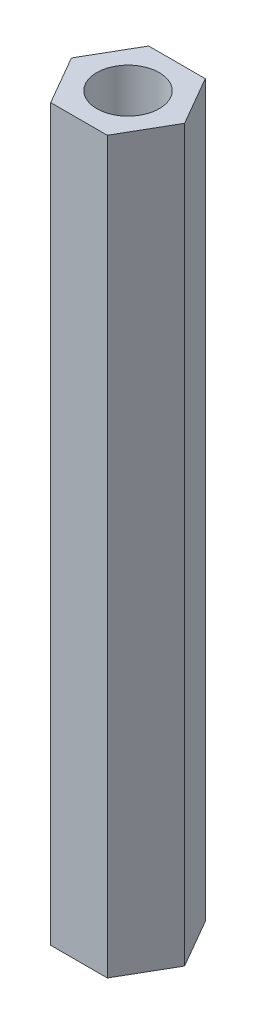
SolidWorks part; units mm, degrees
material "Brass"
ref_plane "Front Plane" through (0, 0, 0) normal (0, 0, 1) x (1, 0, 0)
ref_plane "Top Plane" through (0, 0, 0) normal (0, 1, 0) x (1, 0, 0)
ref_plane "Right Plane" through (0, 0, 0) normal (1, 0, 0) x (0, 0, -1)
sketch "Sketch1" plane through (0, 0, 0) normal (0, 1, 0) x (1, 0, 0)
  line L1 (2.7135, 0) -> (1.3568, 2.35)
  line L2 (1.3568, 2.35) -> (-1.3568, 2.35)
  line L3 (-1.3568, 2.35) -> (-2.7135, 0)
  line L4 (-2.7135, 0) -> (-1.3568, -2.35)
  line L5 (-1.3568, -2.35) -> (1.3568, -2.35)
  line L6 (1.3568, -2.35) -> (2.7135, 0)
  circle A0 centre (0, 0) radius 2.35 construction
  circle A1 centre (0, 0) radius 1.5
extrude "Boss-Extrude1" add sketch "Sketch1" along normal blind 35
